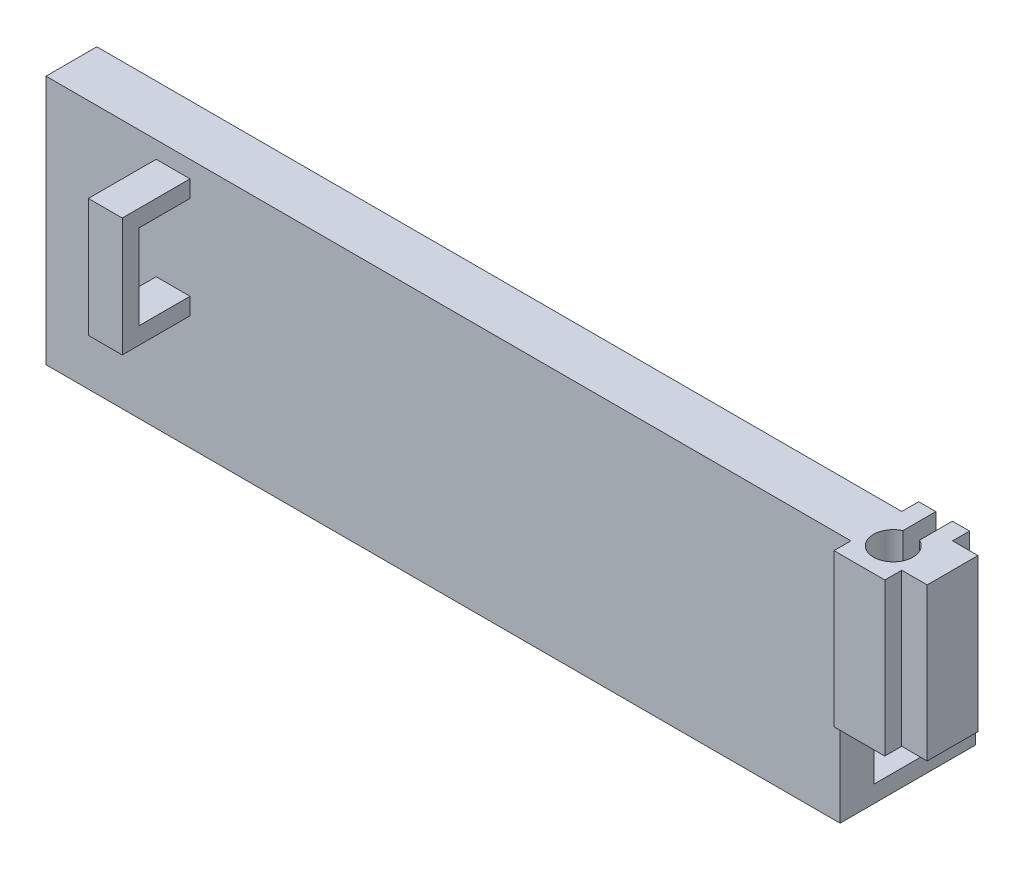
SolidWorks part; units mm, degrees
ref_plane "Front Plane" through (0, 0, 0) normal (0, 0, 1) x (1, 0, 0)
ref_plane "Top Plane" through (0, 0, 0) normal (0, 1, 0) x (1, 0, 0)
ref_plane "Right Plane" through (0, 0, 0) normal (1, 0, 0) x (0, 0, -1)
sketch "Sketch2" plane through (0, 0, 0) normal (0, 0, 1) x (1, 0, 0)
  line L1 (0, 0) -> (53, 0)
  line L2 (0, 0) -> (0, 9)
  line L3 (0, 9) -> (53, 9)
  line L4 (53, 0) -> (53, 9)
  dimension "D1" = 53
  dimension "D2" = 9
extrude "Boss-Extrude1" add sketch "Sketch2" along normal blind 3
sketch "Sketch11" plane through (0, 0, 3) normal (0, 0, 1) x (1, 0, 0)
  line L0 (0, 0) -> (53, 0) construction
  line L1 (53, 9) -> (51, 9)
  line L2 (53, 9) -> (53, 0)
  line L3 (53, 0) -> (51, 0)
  line L4 (51, 9) -> (51, 0)
  dimension "D1" = 2
extrude "Cut-Extrude3" cut sketch "Sketch11" against normal blind 5
sketch "Sketch12" plane through (0, 0, 3) normal (0, 0, 1) x (1, 0, 0)
  line L0 (51, 9) -> (0, 9) construction
  line L1 (46.5, 9) -> (49.5, 9)
  line L2 (46.5, 9) -> (46.5, 0)
  line L3 (46.5, 0) -> (49.5, 0)
  line L4 (49.5, 9) -> (49.5, 0)
  line L5 (0, 0) -> (51, 0) construction
  line L6 (51, 9) -> (51, 0) construction
  dimension "D1" = 3
  dimension "D2" = 1.5
extrude "Boss-Extrude7" add sketch "Sketch12" along normal blind 1
sketch "Sketch13" plane through (0, 0, 3) normal (0, 0, 1) x (1, 0, 0)
  line L0 (0, 9) -> (0, 7) construction
  line L1 (46.5, 9) -> (0, 9) construction
  line L2 (0, 9) -> (0, 0) construction
  line L3 (0, 7) -> (6.5, 7) construction
  line L4 (6.5, 7) -> (6.5, 2) construction
  line L5 (6.5, 2) -> (0, 2) construction
  line L6 (0, 2) -> (0, 0) construction
  line L7 (0, 0) -> (46.5, 0) construction
  line L8 (6.5, 7) -> (7.5, 7)
  line L9 (6.5, 7) -> (6.5, 8)
  line L10 (6.5, 8) -> (7.5, 8)
  line L11 (7.5, 7) -> (7.5, 8)
  line L12 (6.5, 2) -> (7.5, 2)
  line L13 (6.5, 2) -> (6.5, 1)
  line L14 (6.5, 1) -> (7.5, 1)
  line L15 (7.5, 2) -> (7.5, 1)
  dimension "D1" = 2
  dimension "D2" = 6.5
  dimension "D3" = 5
  dimension "D4" = 1
  dimension "D5" = 1
  dimension "D6" = 1
  dimension "D7" = 1
  dimension "D8" = 1
extrude "Boss-Extrude8" add sketch "Sketch13" along normal blind 4
sketch "Sketch14" plane through (0, 7, 0) normal (0, -1, 0) x (1, 0, 0)
  line L0 (7.5, 7) -> (7.5, 3) construction
  line L1 (6.5, 7) -> (7.5, 7)
  line L2 (6.5, 7) -> (6.5, 6)
  line L3 (6.5, 6) -> (7.5, 6)
  line L4 (7.5, 7) -> (7.5, 6)
  dimension "D1" = 1
extrude "Boss-Extrude9" add sketch "Sketch14" along normal up to surface (5 mm away) up to face at (7, 2, 5)
sketch "Sketch15" plane through (0, 0, 0) normal (0, -1, 0) x (1, 0, 0)
  line L0 (0, 0) -> (51, 0) construction
  line L1 (45.8622, 0) -> (0, 0)
  line L2 (45.8622, 0) -> (45.8622, 3)
  line L3 (45.8622, 3) -> (0, 3)
  line L4 (0, 0) -> (0, 3)
extrude "Boss-Extrude10" add sketch "Sketch15" along normal blind 1.5
sketch "Sketch24" plane through (0, 9, 0) normal (0, 1, 0) x (1, 0, 0)
  line L0 (46.5, -3) -> (46.5, 0) construction
  line L1 (51, 0) -> (0, 0) construction
  line L2 (49.5, -3) -> (49.5, 0) construction
  line L3 (51, 0) -> (51, -3) construction
  line L4 (49.5, -4) -> (46.5, -4) construction
  circle A0 centre (48, -2) radius 1.1679
  point P14 (48, -4)
  dimension "D2" = 2
  dimension "D1" = 3
sketch "Sketch25" plane through (0, 0, 0) normal (0, 0, -1) x (-1, 0, 0)
  line L1 (-49.5, 9) -> (-46.5, 9)
  line L2 (-49.5, 9) -> (-49.5, 0)
  line L3 (-49.5, 0) -> (-46.5, 0)
  line L4 (-46.5, 9) -> (-46.5, 0)
extrude "Boss-Extrude13" add sketch "Sketch25" along normal blind 1
extrude "Cut-Extrude7" cut sketch "Sketch24" against normal up to surface (9 mm away) up to face at (48.1437, 0, 1.5)
sketch "Sketch26" plane through (0, 9, 0) normal (0, 1, 0) x (1, 0, 0)
  line L0 (47.5108, -0.9395) -> (47.5108, 1) construction
  line L1 (46.5, 1) -> (49.5, 1) construction
  line L2 (47.5108, -0.9395) -> (48.4892, -0.9395) construction
  line L3 (48.4892, -0.9395) -> (48.4892, 1) construction
  line L5 (47.5108, 1) -> (48.4892, 1)
  line L6 (47.5108, 1) -> (47.5108, -0.9395)
  line L7 (47.5108, -0.9395) -> (48.4892, -0.9395)
  line L8 (48.4892, 1) -> (48.4892, -0.9395)
  circle A0 centre (48, -2) radius 1.1679 construction
extrude "Cut-Extrude8" cut sketch "Sketch26" against normal up to surface (9 mm away) up to face at (48, 0, 3.1679)
sketch "Sketch27" plane through (0, -1.5, 0) normal (0, -1, 0) x (1, 0, 0)
  line L1 (0, 3) -> (45.8622, 3)
  line L2 (0, 3) -> (0, 0)
  line L3 (0, 0) -> (45.8622, 0)
  line L4 (45.8622, 3) -> (45.8622, 0)
extrude "Boss-Extrude14" add sketch "Sketch27" along normal blind 2
sketch "Sketch28" plane through (0, -3.5, 0) normal (0, -1, 0) x (1, 0, 0)
  line L0 (0, 0) -> (45.8622, 0) construction
  line L1 (2.3089, 0) -> (43.5337, 0)
  line L2 (2.3089, 0) -> (2.3089, 1)
  line L3 (2.3089, 1) -> (43.5337, 1)
  line L4 (43.5337, 0) -> (43.5337, 1)
  dimension "D1" = 1
extrude "Cut-Extrude9" cut sketch "Sketch28" against normal blind 1.5
sketch "Sketch29" plane through (0, 0, 0) normal (-1, 0, 0) x (0, 0, 1)
  line L1 (0, 9) -> (3, 9)
  line L2 (0, 9) -> (0, -3.5)
  line L3 (0, -3.5) -> (3, -3.5)
  line L4 (3, 9) -> (3, -3.5)
extrude "Boss-Extrude15" add sketch "Sketch29" along normal blind 1
sketch "Sketch30" plane through (6.5, 0, 0) normal (-1, 0, 0) x (0, 0, 1)
  line L0 (3, 8) -> (3, 7)
  line L1 (3, 7) -> (6, 7)
  line L2 (6, 7) -> (6, 2)
  line L3 (6, 2) -> (3, 2)
  line L4 (3, 2) -> (3, 1)
  line L5 (3, 1) -> (7, 1)
  line L6 (7, 1) -> (7, 8)
  line L7 (7, 8) -> (3, 8)
extrude "Boss-Extrude16" add sketch "Sketch30" along normal blind 1
sketch "Sketch31" plane through (0, -3.5, 0) normal (0, -1, 0) x (1, 0, 0)
  line L1 (43.5337, 1) -> (45.8622, 1)
  line L2 (43.5337, 1) -> (43.5337, 0)
  line L3 (43.5337, 0) -> (45.8622, 0)
  line L4 (45.8622, 1) -> (45.8622, 0)
extrude "Cut-Extrude10" cut sketch "Sketch31" against normal up to surface (1.5 mm away) up to face at (22.9213, -2, 0.5)
sketch "Sketch32" plane through (0, -3.5, 0) normal (0, -1, 0) x (1, 0, 0)
  line L0 (-1, 3) -> (-1, 0)
  line L1 (-1, 0) -> (2.3089, 0)
  line L2 (2.3089, 0) -> (2.3089, 1)
  line L3 (2.3089, 1) -> (45.8622, 1)
  line L4 (45.8622, 1) -> (45.8622, 3)
  line L5 (45.8622, 3) -> (-1, 3)
extrude "Boss-Extrude17" add sketch "Sketch32" along normal blind 2
sketch "Sketch34" plane through (0, 0, 3) normal (0, 0, 1) x (1, 0, 0)
  line L1 (-1, -5.5) -> (45.86, -5.5)
  line L2 (-1, -5.5) -> (-1, -7)
  line L3 (-1, -7) -> (45.86, -7)
  line L4 (45.86, -5.5) -> (45.86, -7)
  dimension "D1" = 46.86
  dimension "D2" = 1.5
extrude "Boss-Extrude18" add sketch "Sketch34" against normal up to surface (3 mm away) up to face at (23.4178, 0.375, 0)
sketch "Sketch35" plane through (0, 0, 0) normal (0, 0, -1) x (-1, 0, 0)
  line L0 (-45.8622, -2) -> (-45.8622, 0) construction
  line L1 (-45.8622, -0.75) -> (-2.3089, -0.75)
  line L2 (-45.8622, -0.75) -> (-45.8622, -2)
  line L3 (-45.8622, -2) -> (-2.3089, -2)
  line L4 (-2.3089, -0.75) -> (-2.3089, -2)
  dimension "D1" = 1.25
extrude "Cut-Extrude11" cut sketch "Sketch35" against normal up to surface (1 mm away) up to face at (18.6413, -3.3125, 1)
sketch "Sketch36" plane through (0, 0, 0) normal (0, 0, -1) x (-1, 0, 0)
  line L0 (1, 9) -> (1, -7) construction
  line L1 (-45.86, -7) -> (1, -7)
  line L2 (-45.86, -7) -> (-45.86, -3.25)
  line L3 (-45.86, -3.25) -> (1, -3.25)
  line L4 (1, -7) -> (1, -3.25)
  line L5 (-2.3089, -0.75) -> (-45.8622, -0.75) construction
  dimension "D1" = 2.5
extrude "Cut-Extrude12" cut sketch "Sketch36" against normal up to surface (3 mm away) up to face at (50.25, 4.5, 3)
sketch "Sketch37" plane through (45.86, 0, 0) normal (-1, 0, 0) x (0, 0, 1)
  line L0 (3, -5.5) -> (3, -3.25) construction
  line L1 (1, -3.25) -> (3, -3.25)
  line L2 (1, -3.25) -> (1, -5.5)
  line L3 (1, -5.5) -> (3, -5.5)
  line L4 (3, -3.25) -> (3, -5.5)
extrude "Cut-Extrude13" cut sketch "Sketch37" against normal blind 10
sketch "Sketch41" plane through (0, -3.25, 0) normal (0, -1, 0) x (1, 0, 0)
  line L0 (-1, 0) -> (-1, 3)
  line L1 (-1, 3) -> (45.8622, 3)
  line L2 (45.8622, 3) -> (45.8622, 1)
  line L3 (45.8622, 1) -> (2.3089, 1)
  line L4 (2.3089, 1) -> (2.3089, 0)
  line L5 (2.3089, 0) -> (-1, 0)
extrude "Boss-Extrude19" add sketch "Sketch41" along normal blind 2.5
sketch "Sketch42" plane through (0, 0, 1) normal (0, 0, -1) x (-1, 0, 0)
  line L0 (-45.8622, -4.75) -> (-2.3089, -4.75)
  line L1 (-45.8622, -0.75) -> (-45.8622, -5.75) construction
  line L2 (-2.3089, -0.75) -> (-2.3089, -5.75) construction
  line L3 (-2.3089, -5.75) -> (-45.8622, -5.75) construction
  line L4 (-45.8622, -4.75) -> (-45.8622, -5.75)
  line L5 (-45.8622, -5.75) -> (-2.3089, -5.75)
  line L6 (-2.3089, -5.75) -> (-2.3089, -4.75)
  dimension "D1" = 1
extrude "Boss-Extrude20" add sketch "Sketch42" along normal blind 1 contours L0 L6 L5 L4
sketch "Sketch44" plane through (0, 0, 0) normal (0, 0, -1) x (-1, 0, 0)
  line L1 (-45.8622, -4.75) -> (1, -4.75)
  line L2 (-45.8622, -4.75) -> (-45.8622, -5.75)
  line L3 (-45.8622, -5.75) -> (1, -5.75)
  line L4 (1, -4.75) -> (1, -5.75)
extrude "Boss-Extrude21" add sketch "Sketch44" along normal blind 5
sketch "Sketch46" plane through (0, -0.75, 0) normal (0, -1, 0) x (1, 0, 0)
  line L1 (45.8622, 1) -> (2.3089, 1)
  line L2 (45.8622, 1) -> (45.8622, 0)
  line L3 (45.8622, 0) -> (2.3089, 0)
  line L4 (2.3089, 1) -> (2.3089, 0)
extrude "Boss-Extrude22" add sketch "Sketch46" along normal blind 1
